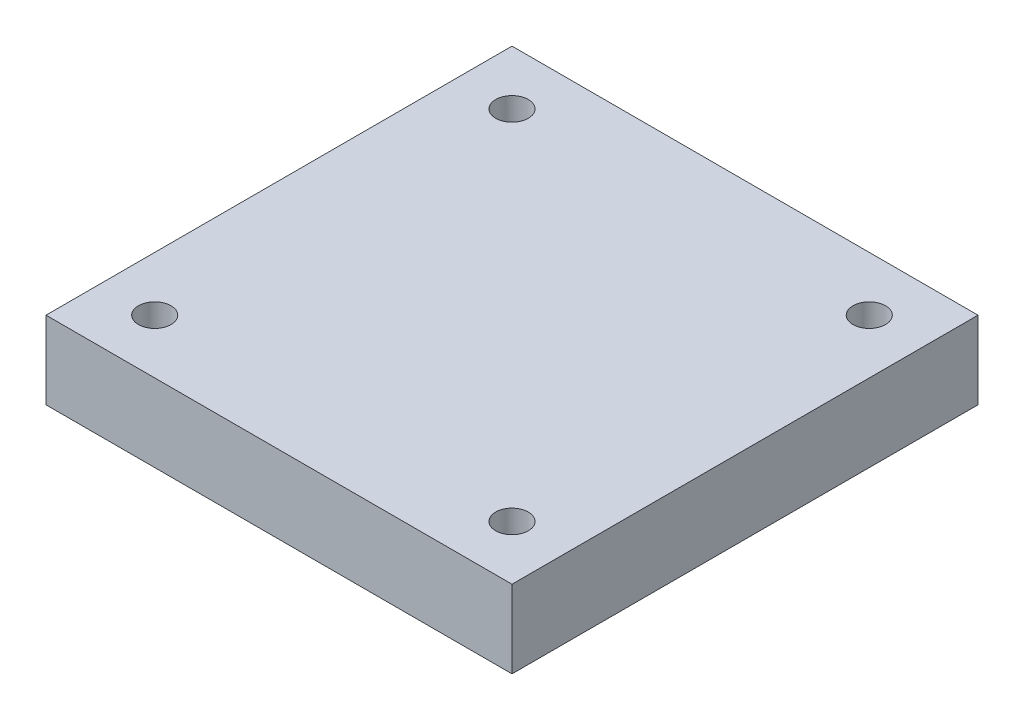
SolidWorks part; units mm, degrees
ref_plane "Front Plane" through (0, 0, 0) normal (0, 0, 1) x (1, 0, 0)
ref_plane "Top Plane" through (0, 0, 0) normal (0, 1, 0) x (1, 0, 0)
ref_plane "Right Plane" through (0, 0, 0) normal (1, 0, 0) x (0, 0, -1)
sketch "Sketch1" plane through (0, 0, 0) normal (0, 1, 0) x (1, 0, 0)
  line L1 (-30, -30) -> (30, -30)
  line L2 (-30, -30) -> (-30, 30)
  line L3 (-30, 30) -> (30, 30)
  line L4 (30, -30) -> (30, 30)
  line L5 (-30, -30) -> (30, 30) construction
  line L6 (-30, 30) -> (30, -30) construction
  point P0 (0, 0)
  dimension "D1" = 60
  dimension "D2" = 60
extrude "Boss-Extrude1" add sketch "Sketch1" along normal blind 10
sketch "Sketch2" plane through (0, 10, 0) normal (0, 1, 0) x (1, 0, 0)
  line L1 (-23, -23) -> (23, -23)
  line L2 (-23, -23) -> (-23, 23)
  line L3 (-23, 23) -> (23, 23)
  line L4 (23, -23) -> (23, 23)
  line L5 (-23, -23) -> (23, 23) construction
  line L6 (-23, 23) -> (23, -23) construction
  circle A0 centre (0, -21.2132) radius 4
  point P0 (0, 0)
  dimension "D4" = 8
  dimension "D1" = 46
  dimension "D2" = 15
  dimension "D3" = 15
extrude "Cut-Extrude1" [suppressed] cut sketch "Sketch2" against normal through all contours A0
pattern_linear "LPattern1" [suppressed] count 3 spacing 15 along (0.7071, 0, -0.7071) count 3 spacing 15 along (0.7071, 0, 0.7071)
hole_wizard "CBORE for M5 Hex Socket Head Cap Screw1" [suppressed] positions "3DSketch1" profile "Sketch3" counterbore size "M5" standard "ISO"
sketch3d "3DSketch1"
  point P0 (-23, 10, -23)
  point P3 (23, 10, -23)
  point P6 (23, 10, 23)
  point P9 (-23, 10, 23)
sketch "Sketch3" plane through (-23, 10, -23) normal (1, 0, 0) x (0, 0, 1)
  line L0 (0, 0) -> (0, 10)
  line L1 (0, 10) -> (2.75, 10)
  line L3 (2.75, 10) -> (2.75, 5.4)
  line L4 (2.75, 5.4) -> (5, 5.4)
  line L5 (5, 5.4) -> (5, 0)
  line L7 (5, 0) -> (0, 0)
  line L11 (0, -6.35) -> (0, 107.95) construction
  dimension "Thru Hole Dia." = 5.5
  dimension "Thru Hole Depth" = 10
  dimension "C'Bore Dia." = 10
  dimension "C'Bore Depth" = 5.4
hole_wizard "M5 Tapped Hole1" positions "3DSketch2" profile "Sketch4" tap size "M5" standard "ISO" end condition through all
sketch3d "3DSketch2"
  point P0 (-23, 10, -23)
  point P3 (23, 10, -23)
  point P6 (23, 10, 23)
  point P9 (-23, 10, 23)
sketch "Sketch4" plane through (-23, 10, -23) normal (1, 0, 0) x (0, 0, 1)
  line L0 (0, 0) -> (0, 10)
  line L1 (0, 10) -> (2.1, 10)
  line L2 (2.1, 10) -> (2.1, 0)
  line L5 (2.1, 0) -> (0, 0)
  line L11 (0, -6.35) -> (0, 107.95) construction
  dimension "Thru Tap Drill Dia." = 4.2
  dimension "Thru Tap Drill Depth" = 10
cosmetic thread "Hole Thread1" parameters "D2"=5
cosmetic thread "Hole Thread2" parameters "D2"=5
cosmetic thread "Hole Thread3" parameters "D2"=5
cosmetic thread "Hole Thread4" parameters "D2"=5
